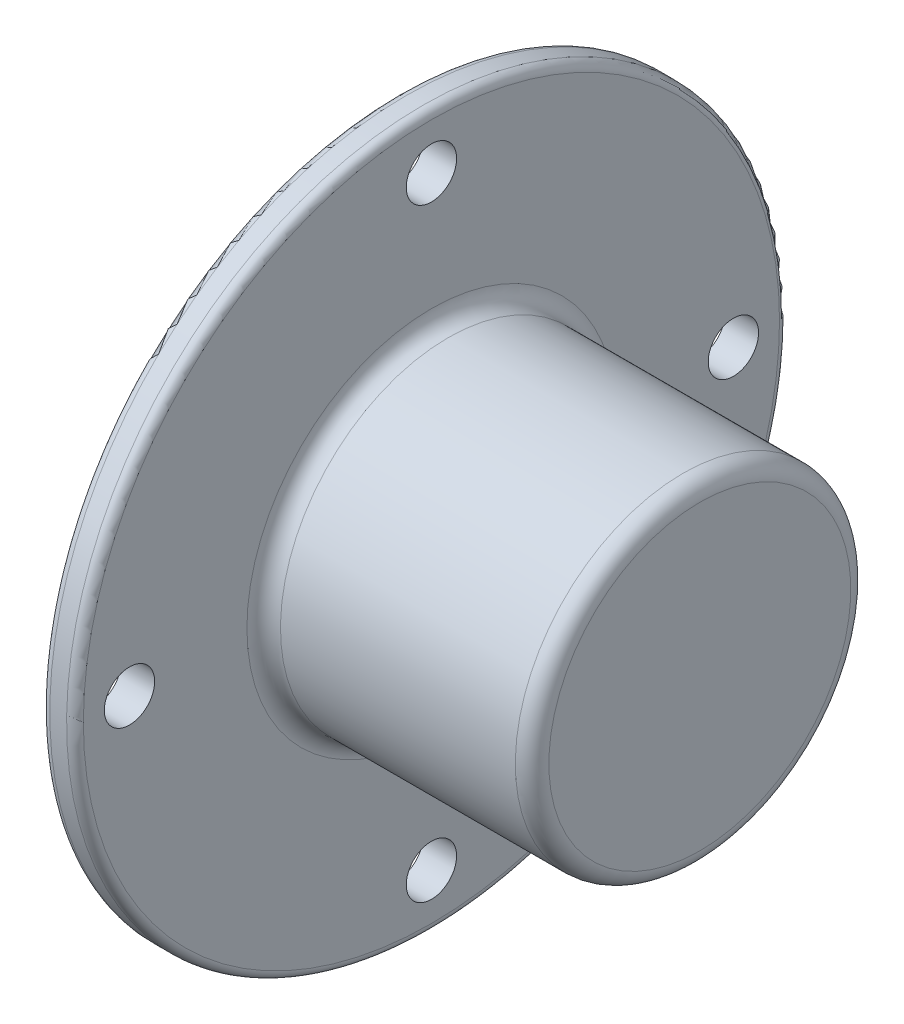
SolidWorks part; units mm, degrees
material "Custom PLA"
ref_plane "Front Plane" through (0, 0, 0) normal (0, 0, 1) x (1, 0, 0)
ref_plane "Top Plane" through (0, 0, 0) normal (0, 1, 0) x (1, 0, 0)
ref_plane "Right Plane" through (0, 0, 0) normal (1, 0, 0) x (0, 0, -1)
sketch "Sketch2" plane through (0, 0, 0) normal (0, 0, 1) x (1, 0, 0)
  line L0 (0, 0) -> (0, 21.25)
  line L1 (0, 21.25) -> (2, 21.25)
  line L2 (2, 21.25) -> (2, 10)
  line L3 (2, 10) -> (18, 10)
  line L4 (18, 10) -> (18, 0)
  line L5 (18, 0) -> (0, 0)
  dimension "D1" = 10
  dimension "D2" = 18
  dimension "D3" = 2
  dimension "D4" = 21.25
revolve "Revolve1" add sketch "Sketch2" angle 360 about L5
sketch "Sketch3" plane through (2, 0, 0) normal (1, 0, 0) x (0, 0, -1)
  line L0 (0, 21.25) -> (0, -21.25) construction
  line L1 (-21.25, 0) -> (21.25, 0) construction
  circle A0 centre (0, 0) radius 21.25 construction
  circle A1 centre (0, 0) radius 18 construction
  circle A2 centre (0, 18) radius 1.5
  dimension "D1" = 36
  dimension "D2" = 3
extrude "Cut-Extrude1" cut sketch "Sketch3" against normal up to next
pattern_circular "CirPattern1" count 4 over 360 about axis through (0, 0, 0) along (1, 0, 0) of "Cut-Extrude1"
fillet "Fillet1" radius 0.5 2 edges at (2, 21.25, 0) (0, 21.25, 0)
fillet "Fillet2" radius 1 2 edges at (18, 10, 0) (2, 10, 0)
